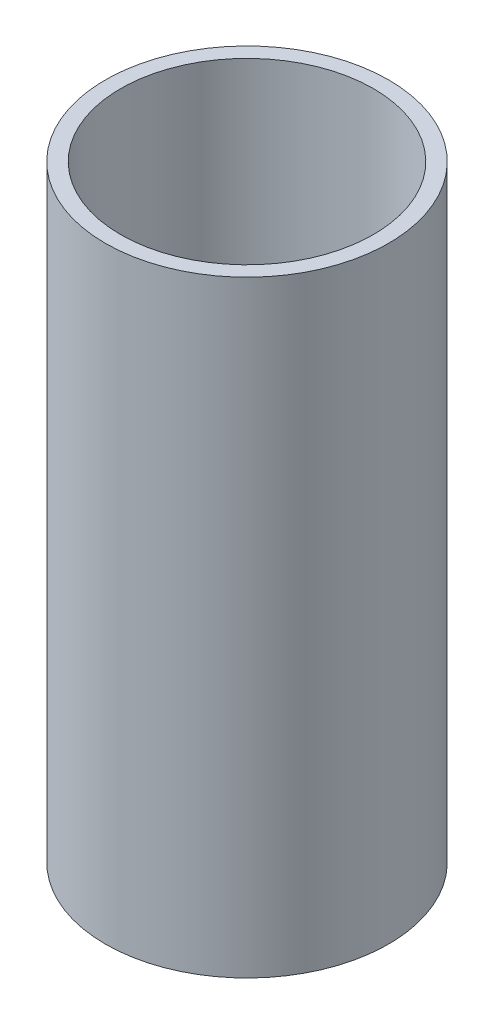
SolidWorks part; units mm, degrees
material "7075-T6 (SN)"
ref_plane "Alzado" through (0, 0, 0) normal (0, 0, 1) x (1, 0, 0)
ref_plane "Planta" through (0, 0, 0) normal (0, 1, 0) x (1, 0, 0)
ref_plane "Vista lateral" through (0, 0, 0) normal (1, 0, 0) x (0, 0, -1)
sketch "Croquis1" plane through (0, 0, 0) normal (0, 1, 0) x (1, 0, 0)
  circle A0 centre (0, 0) radius 14
  circle A1 centre (0, 0) radius 12.5
  dimension "D1" = 28
  dimension "D2" = 25
extrude "Saliente-Extruir1" add sketch "Croquis1" along normal blind 60
